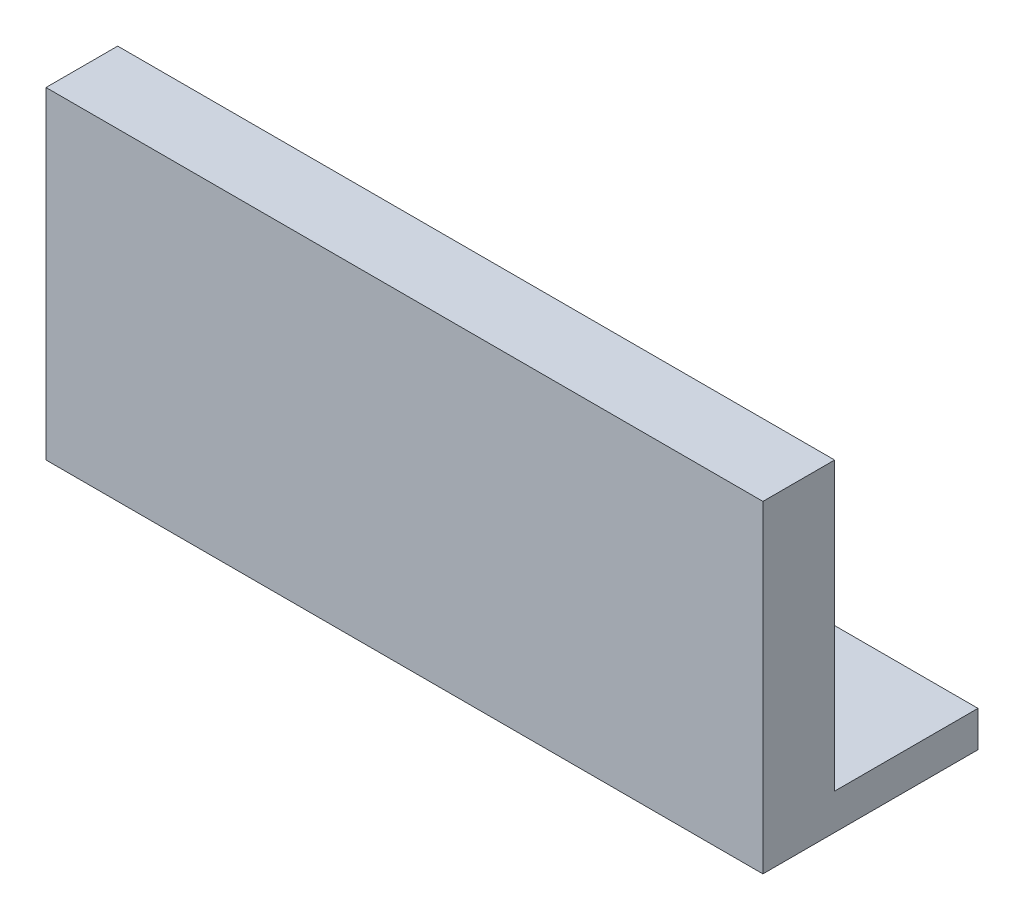
SolidWorks part; units mm, degrees
material "201 Acero inoxidable recocido (SS)"
ref_plane "Alzado" through (0, 0, 0) normal (0, 0, 1) x (1, 0, 0)
ref_plane "Planta" through (0, 0, 0) normal (0, 1, 0) x (1, 0, 0)
ref_plane "Vista lateral" through (0, 0, 0) normal (1, 0, 0) x (0, 0, -1)
sketch "Croquis1" plane through (0, 0, 0) normal (1, 0, 0) x (0, 0, -1)
  line L0 (0, 0) -> (0, 450)
  line L1 (0, 450) -> (100, 450)
  line L2 (100, 450) -> (100, 50)
  line L3 (100, 50) -> (300, 50)
  line L4 (300, 50) -> (300, 0)
  line L5 (300, 0) -> (0, 0)
  dimension "D1" = 450
  dimension "D2" = 300
  dimension "D3" = 100
  dimension "D4" = 50
  dimension "D5" = 200
extrude "Saliente-Extruir1" add sketch "Croquis1" along normal blind 1000
